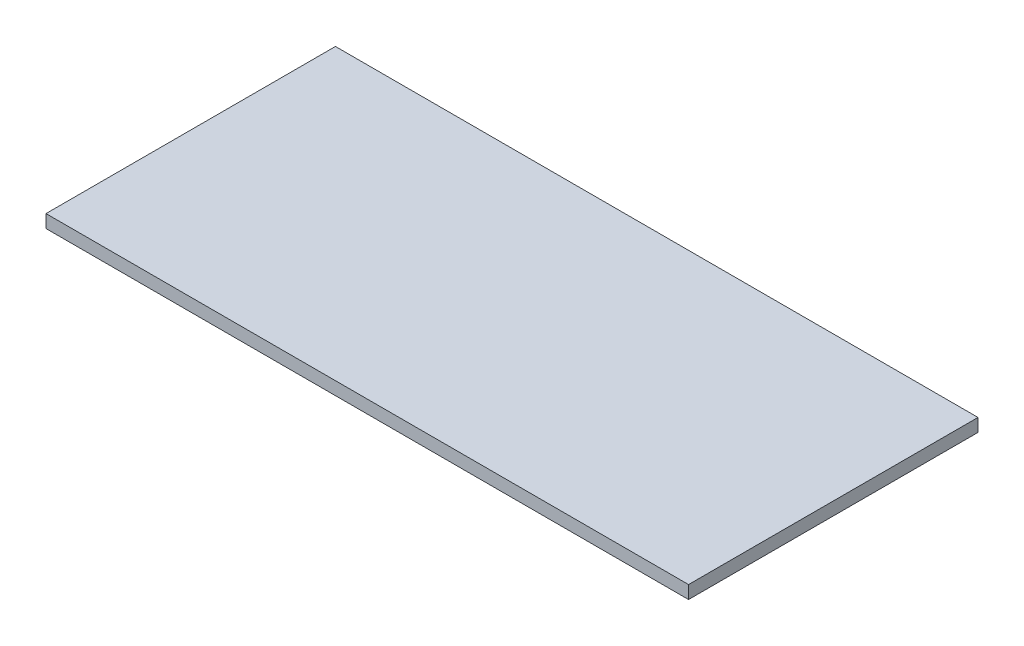
SolidWorks part; units mm, degrees
ref_plane "Front Plane" through (0, 0, 0) normal (0, 0, 1) x (1, 0, 0)
ref_plane "Top Plane" through (0, 0, 0) normal (0, 1, 0) x (1, 0, 0)
ref_plane "Right Plane" through (0, 0, 0) normal (1, 0, 0) x (0, 0, -1)
sketch "Sketch1" plane through (0, 0, 0) normal (0, 1, 0) x (1, 0, 0)
  line L1 (-245, -110.363) -> (245, -110.363)
  line L2 (-245, -110.363) -> (-245, 110.363)
  line L3 (-245, 110.363) -> (245, 110.363)
  line L4 (245, -110.363) -> (245, 110.363)
  line L5 (-245, -110.363) -> (245, 110.363) construction
  line L6 (-245, 110.363) -> (245, -110.363) construction
  point P0 (0, 0)
  dimension "D1" = 490
  dimension "D2" = 220.726
extrude "Boss-Extrude1" add sketch "Sketch1" along normal blind 9.906
